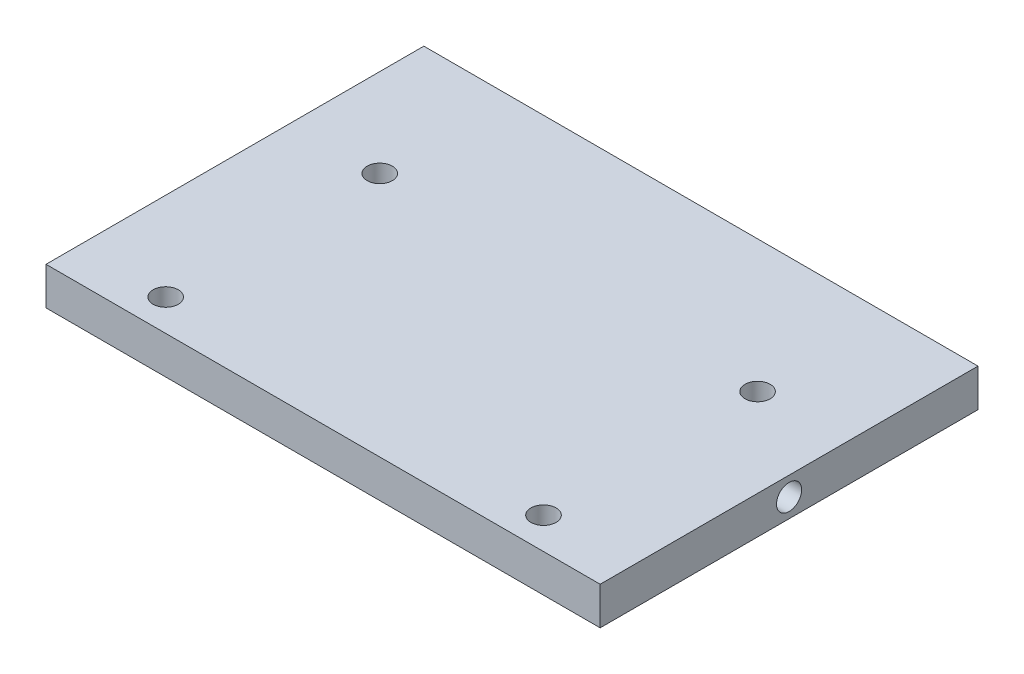
SolidWorks part; units mm, degrees
ref_plane "Front Plane" through (0, 0, 0) normal (0, 0, 1) x (1, 0, 0)
ref_plane "Top Plane" through (0, 0, 0) normal (0, 1, 0) x (1, 0, 0)
ref_plane "Right Plane" through (0, 0, 0) normal (1, 0, 0) x (0, 0, -1)
sketch "Sketch1" plane through (0, 0, 0) normal (0, 1, 0) x (1, 0, 0)
  line L1 (-22, 15) -> (22, 15)
  line L2 (-22, 15) -> (-22, -15)
  line L3 (-22, -15) -> (22, -15)
  line L4 (22, 15) -> (22, -15)
  line L5 (-22, 15) -> (22, -15) construction
  line L6 (-22, -15) -> (22, 15) construction
  point P0 (0, 0)
  dimension "D1" = 44
  dimension "D2" = 30
extrude "Boss-Extrude1" add sketch "Sketch1" along normal blind 3 contours L1 L4 L3 L2
sketch "Sketch2" plane through (-22, 0, 0) normal (-1, 0, 0) x (0, 0, 1)
  line L0 (-15, 1.5) -> (15, 1.5) construction
  line L1 (-15, 3) -> (-15, 0) construction
  line L2 (15, 3) -> (15, 0) construction
  circle A0 centre (0, 1.5) radius 1
  point P8 (0, 0)
  point P9 (0, 1.5)
  point P10 (0, 1.5)
  point P11 (0, 1.5)
  dimension "D1" = 2
extrude "Cut-Extrude1" cut sketch "Sketch2" against normal blind 5
mirror "Mirror1" about plane through (0, 0, 0) normal (1, 0, 0) of "Cut-Extrude1"
sketch "Sketch3" plane through (0, 0, 0) normal (0, -1, 0) x (-1, 0, 0)
  line L1 (-15, 4.5) -> (15, 4.5) construction
  line L2 (-15, -12.5) -> (15, -12.5) construction
  line L3 (0, 15) -> (0, -15) construction
  line L4 (22, 15) -> (-22, 15) construction
  line L5 (22, -15) -> (-22, -15) construction
  circle A0 centre (15, 4.5) radius 1
  circle A1 centre (15, -12.5) radius 1
  circle A2 centre (-15, -12.5) radius 1
  circle A3 centre (-15, 4.5) radius 1
  point P18 (0, 4.5)
  point P19 (0, 0)
  dimension "D3" = 2
  dimension "D4" = 2
  dimension "D5" = 2
  dimension "D6" = 2
  dimension "D1" = 30
  dimension "D2" = 17
  dimension "D7" = 2.5
extrude "Cut-Extrude2" cut sketch "Sketch3" against normal blind 5
